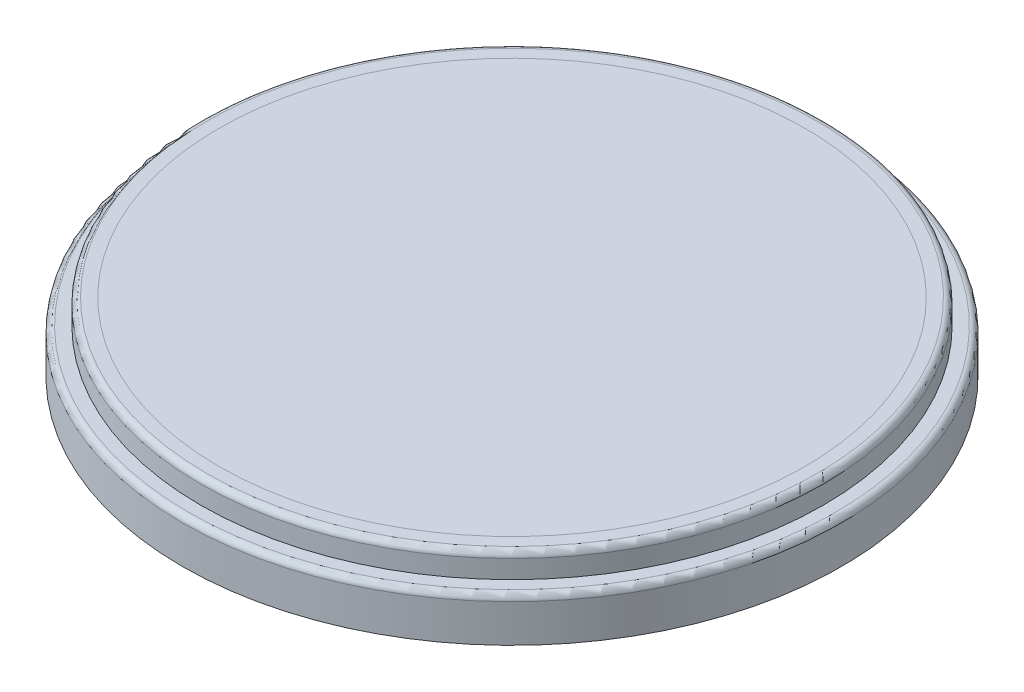
SolidWorks part; units mm, degrees
ref_plane "Front Plane" through (0, 0, 0) normal (0, 0, 1) x (1, 0, 0)
ref_plane "Top Plane" through (0, 0, 0) normal (0, 1, 0) x (1, 0, 0)
ref_plane "Right Plane" through (0, 0, 0) normal (1, 0, 0) x (0, 0, -1)
sketch "Sketch1" plane through (0, 0, 0) normal (0, 1, 0) x (1, 0, 0)
  circle A0 centre (0, 0) radius 27
  circle A1 centre (0, 0) radius 25.5
  dimension "D1" = 54
  dimension "D2" = 1.5
extrude "Boss-Extrude1" add sketch "Sketch1" along normal blind 3.6
sketch "Sketch2" plane through (0, 3.6, 0) normal (0, 1, 0) x (1, 0, 0)
  circle A0 centre (0, 0) radius 25.5
  circle A1 centre (0, 0) radius 24
  dimension "D1" = 51
  dimension "D2" = 1.5
extrude "Boss-Extrude2" add sketch "Sketch2" along normal blind 2
fillet "Fillet2" radius 0.5 2 edges at (0, 3.6, 24) (0, 5.6, 25.5)
fillet "Fillet4" radius 0.5 1 edges at (0, 3.6, 27)
sketch "Sketch3" plane through (0, 5.6, 0) normal (0, 1, 0) x (1, 0, 0)
  circle A0 centre (0, 0) radius 24
  circle A1 centre (0, 0) radius 24 construction
extrude "Boss-Extrude4" add sketch "Sketch3" against normal blind 1 separate body
